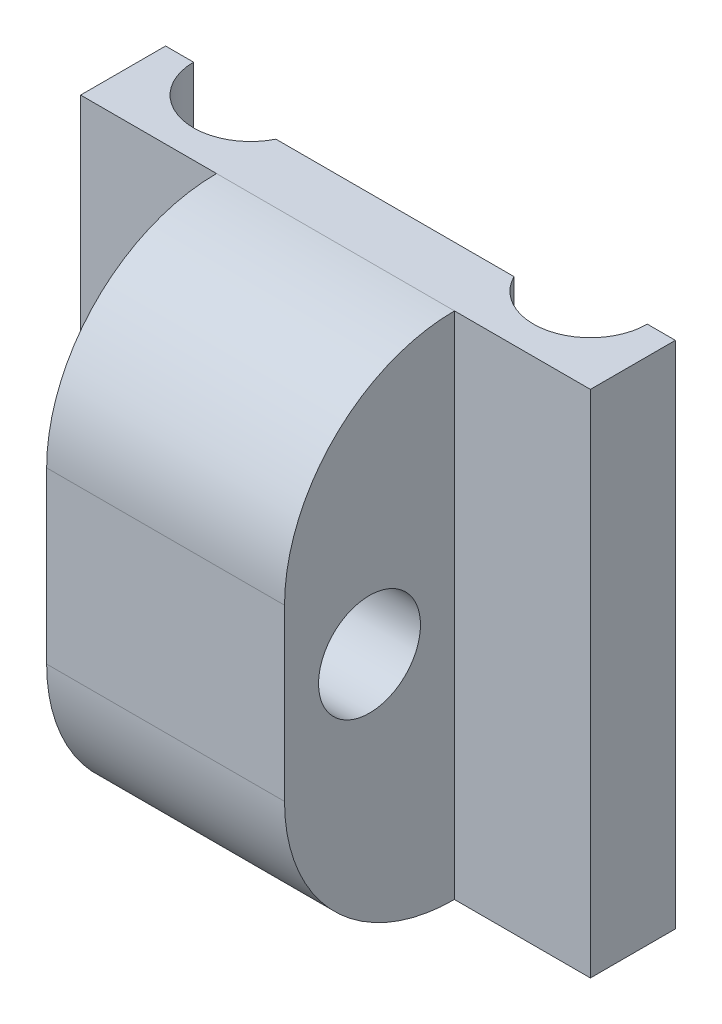
SolidWorks part; units mm, degrees
ref_plane "Front Plane" through (0, 0, 0) normal (0, 0, 1) x (1, 0, 0)
ref_plane "Top Plane" through (0, 0, 0) normal (0, 1, 0) x (1, 0, 0)
ref_plane "Right Plane" through (0, 0, 0) normal (1, 0, 0) x (0, 0, -1)
sketch "Sketch1" plane through (0, 0, 0) normal (0, 1, 0) x (1, 0, 0)
  line L0 (8.35, 15) -> (21.65, 15)
  line L1 (0, 0) -> (30, 0)
  line L2 (0, 0) -> (0, 15)
  line L3 (0, 15) -> (1.65, 15)
  line L4 (30, 0) -> (30, 15)
  line L5 (28.35, 15) -> (30, 15)
  arc A0 (1.65, 15) -> (8.35, 15) centre (5, 15) ccw
  arc A1 (21.65, 15) -> (28.35, 15) centre (25, 15) ccw
  point P9 (0, 0)
  dimension "D3" = 20
  dimension "D1" = 30
  dimension "D2" = 15
  dimension "D4" = 5
extrude "Boss-Extrude1" add sketch "Sketch1" along normal blind 30
sketch "Sketch2" plane through (0, 30, 0) normal (0, 1, 0) x (1, 0, 0)
sketch "Sketch3" plane through (0, 0, 0) normal (-1, 0, 0) x (0, 0, 1)
  circle A0 centre (-5, 15) radius 3
extrude "Cut-Extrude2" cut sketch "Sketch3" against normal through all both and the other way through all
sketch "Sketch4" plane through (0, 0, 0) normal (0, -1, 0) x (1, 0, 0)
  line L1 (6.7785, -15.2216) -> (22.6453, -15.2216)
  line L2 (6.7785, -15.2216) -> (6.7785, -13.5)
  line L3 (6.7785, -13.5) -> (22.6453, -13.5)
  line L4 (22.6453, -15.2216) -> (22.6453, -13.5)
  point P4 (0, 0)
extrude "Cut-Extrude3" cut sketch "Sketch4" against normal through all both and the other way through all
fillet "Fillet1" radius 10 2 edges at (15, 30, 0) (15, 0, 0)
sketch "Sketch5" plane through (0, 0, 0) normal (0, -1, 0) x (1, 0, 0)
  line L0 (30, -10) -> (0, -10) construction
  line L1 (0, 0) -> (8, 0)
  line L2 (0, 0) -> (0, -10)
  line L3 (0, -10) -> (8, -10)
  line L4 (8, 0) -> (8, -10)
  line L6 (30, 0) -> (22, 0)
  line L7 (30, 0) -> (30, -10)
  line L8 (30, -10) -> (22, -10)
  line L9 (22, 0) -> (22, -10)
  dimension "D1" = 8
  dimension "D2" = 8
extrude "Cut-Extrude4" cut sketch "Sketch5" against normal through all both and the other way through all
